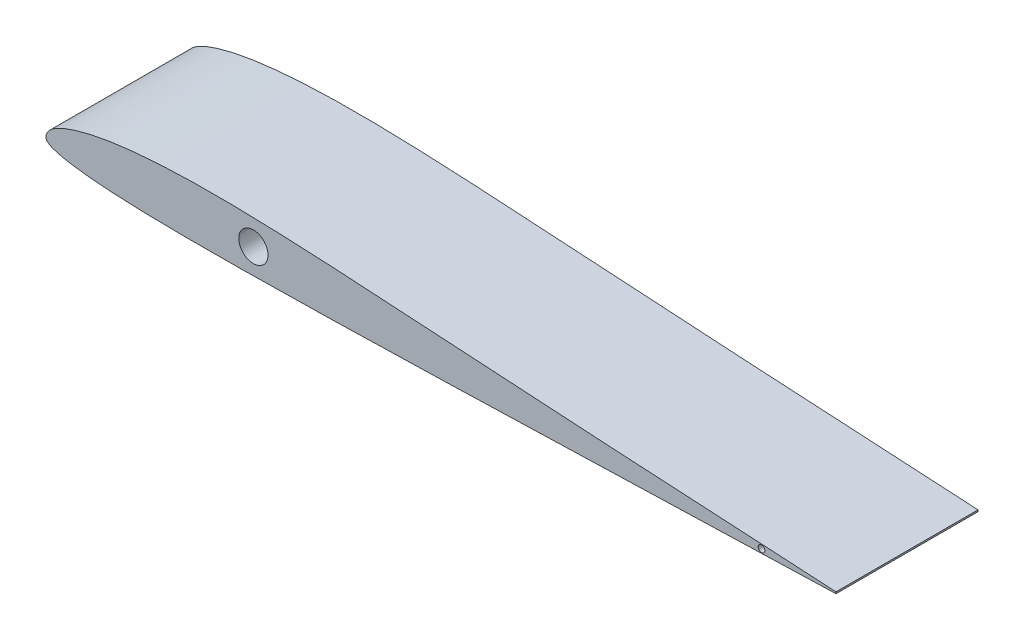
SolidWorks part; units mm, degrees
material "Polyurethane Foam Flexible"
ref_plane "Front Plane" through (0, 0, 0) normal (0, 0, 1) x (1, 0, 0)
ref_plane "Top Plane" through (0, 0, 0) normal (0, 1, 0) x (1, 0, 0)
ref_plane "Right Plane" through (0, 0, 0) normal (1, 0, 0) x (0, 0, -1)
curve "ht32-8-imported"
  spline degree 3 poles (203.2026, 0.2115, 0) (202.75, 0.2358, 0) (201.4822, 0.3036, 0) (199.2299, 0.4276, 0) (196.3046, 0.5865, 0) (192.9787, 0.7694, 0) (189.375, 0.9706, 0) (185.6129, 1.1785, 0) (181.7737, 1.3957, 0) (177.8996, 1.6147, 0) (174.01, 1.8354, 0) (170.1132, 2.0552, 0) (166.2133, 2.2775, 0) (162.3117, 2.4986, 0) (158.4107, 2.722, 0) (154.5106, 2.9441, 0) (150.6142, 3.1678, 0) (146.7204, 3.3936, 0) (142.8309, 3.617, 0) (138.944, 3.8454, 0) (135.0595, 4.0721, 0) (131.1775, 4.3012, 0) (127.2967, 4.5315, 0) (123.4189, 4.7649, 0) (119.5421, 5.0008, 0) (115.6675, 5.2398, 0) (111.7949, 5.4816, 0) (107.9236, 5.7247, 0) (104.0572, 5.9681, 0) (100.1894, 6.212, 0) (96.3188, 6.4543, 0) (92.4477, 6.6946, 0) (88.584, 6.9322, 0) (84.7415, 7.1637, 0) (80.9229, 7.3889, 0) (77.3978, 7.5906, 0) (74.5229, 7.7493, 0) (71.9946, 7.8843, 0) (69.1241, 8.0324, 0) (65.5083, 8.2076, 0) (61.4852, 8.3831, 0) (57.5218, 8.5328, 0) (53.6734, 8.652, 0) (49.9058, 8.739, 0) (46.181, 8.7912, 0) (42.491, 8.8047, 0) (38.8468, 8.7742, 0) (35.2596, 8.6962, 0) (31.7561, 8.5671, 0) (28.3661, 8.3856, 0) (25.1292, 8.152, 0) (22.0798, 7.8688, 0) (19.2587, 7.5428, 0) (16.7019, 7.1837, 0) (14.4336, 6.8058, 0) (12.4541, 6.4216, 0) (10.7471, 6.0418, 0) (9.283, 5.6741, 0) (8.0264, 5.3216, 0) (6.9394, 4.9844, 0) (5.9876, 4.6599, 0) (5.1429, 4.3427, 0) (4.3754, 4.0301, 0) (3.6577, 3.7081, 0) (2.9646, 3.3607, 0) (2.2868, 2.9708, 0) (1.6384, 2.5305, 0) (1.05, 2.0355, 0) (0.5511, 1.4823, 0) (0.1821, 0.8795, 0) (0.0202, 0.3651, 0) (-0.0065, -0.0193, 0) (0.0194, -0.3136, 0) (0.1268, -0.6144, 0) (0.297, -0.8546, 0) (0.4742, -1.036, 0) (0.6922, -1.2054, 0) (0.9846, -1.3848, 0) (1.3525, -1.5668, 0) (1.7794, -1.7448, 0) (2.2605, -1.9172, 0) (2.8067, -2.0876, 0) (3.4413, -2.2602, 0) (4.1881, -2.438, 0) (5.0669, -2.6215, 0) (6.0922, -2.8069, 0) (7.2766, -2.9931, 0) (8.6343, -3.178, 0) (10.1869, -3.3594, 0) (11.9608, -3.5369, 0) (13.9882, -3.7077, 0) (16.2949, -3.8689, 0) (18.8937, -4.0155, 0) (21.7662, -4.1437, 0) (24.8729, -4.2492, 0) (28.1584, -4.3297, 0) (31.5775, -4.3867, 0) (35.0914, -4.4207, 0) (38.6791, -4.4351, 0) (42.3216, -4.4311, 0) (46.0126, -4.4125, 0) (49.7579, -4.3795, 0) (53.5805, -4.3372, 0) (57.5149, -4.2842, 0) (61.5959, -4.2202, 0) (65.8841, -4.1445, 0) (69.584, -4.0721, 0) (72.8088, -4.005, 0) (75.5799, -3.9448, 0) (78.7708, -3.8727, 0) (82.2137, -3.7909, 0) (85.8123, -3.7021, 0) (89.4548, -3.6091, 0) (93.1502, -3.5116, 0) (96.8889, -3.4111, 0) (100.657, -3.3069, 0) (104.4397, -3.2018, 0) (108.2248, -3.0945, 0) (112.0082, -2.9863, 0) (115.791, -2.8766, 0) (119.5782, -2.7658, 0) (123.3765, -2.6523, 0) (127.1945, -2.5376, 0) (131.0416, -2.42, 0) (134.9198, -2.302, 0) (138.8194, -2.1823, 0) (142.7263, -2.0602, 0) (146.6334, -1.9373, 0) (150.5405, -1.8169, 0) (154.4476, -1.6935, 0) (158.3547, -1.5735, 0) (162.2615, -1.4515, 0) (166.1675, -1.3317, 0) (170.0718, -1.2089, 0) (173.9729, -1.0897, 0) (177.8669, -0.9678, 0) (181.7453, -0.8488, 0) (185.5889, -0.7312, 0) (189.3549, -0.6169, 0) (192.9626, -0.5096, 0) (196.292, -0.413, 0) (199.2203, -0.3248, 0) (201.4752, -0.2617, 0) (202.7443, -0.2247, 0) (203.1974, -0.2115, 0) knots 0 0 0 0 0.003316 0.009286 0.0165 0.024744 0.033651 0.0429 0.052304 0.061778 0.071282 0.080801 0.090326 0.099855 0.109385 0.118907 0.128429 0.137932 0.147436 0.156926 0.166412 0.175898 0.185369 0.194848 0.204314 0.213779 0.223243 0.232695 0.242152 0.25158 0.261042 0.270519 0.279949 0.289356 0.298677 0.307928 0.315183 0.319737 0.326448 0.336207 0.346216 0.355902 0.365219 0.374379 0.383467 0.392467 0.401369 0.410123 0.41871 0.427012 0.434953 0.442447 0.449411 0.455723 0.46133 0.466229 0.470471 0.47412 0.47727 0.480016 0.482444 0.484624 0.486615 0.488504 0.490376 0.492284 0.49422 0.496102 0.497896 0.499646 0.501237 0.501776 0.502457 0.503386 0.504071 0.504595 0.505236 0.506086 0.5071 0.508235 0.509467 0.510837 0.512419 0.514277 0.516452 0.518985 0.521897 0.525221 0.529007 0.53333 0.538261 0.543889 0.550243 0.557299 0.56492 0.57298 0.581338 0.589931 0.598683 0.607581 0.616575 0.625681 0.634977 0.644537 0.654462 0.664831 0.675908 0.681531 0.688425 0.696181 0.704877 0.713615 0.722511 0.731528 0.740655 0.749867 0.759101 0.768335 0.777565 0.786786 0.796016 0.805278 0.814581 0.823955 0.833431 0.842961 0.852492 0.862023 0.871554 0.881085 0.890615 0.900146 0.909675 0.9192 0.928718 0.938223 0.947696 0.9571 0.96635 0.975256 0.9835 0.990713 0.996685 1 1 1 1
sketch "Sketch3" plane through (0, 0, 0) normal (0, 0, 1) x (1, 0, 0)
  line L3 (203.2026, 0.2115) -> (203.1974, -0.2115)
  spline S0 degree 3 poles (334.6154, -3985.5649) (434.4726, 3.4305) (316.9129, -6.0481) (199.2299, 0.4276) (196.3046, 0.5865) (192.9787, 0.7694) (189.375, 0.9706) (185.6129, 1.1785) (181.7737, 1.3957) (177.8996, 1.6147) (174.01, 1.8354) (170.1132, 2.0552) (166.2133, 2.2775) (162.3117, 2.4986) (158.4107, 2.722) (154.5106, 2.9441) (150.6142, 3.1678) (146.7204, 3.3936) (142.8309, 3.617) (138.944, 3.8454) (135.0595, 4.0721) (131.1775, 4.3012) (127.2967, 4.5315) (123.4189, 4.7649) (119.5421, 5.0008) (115.6675, 5.2398) (111.7949, 5.4816) (107.9236, 5.7247) (104.0572, 5.9681) (100.1894, 6.212) (96.3188, 6.4543) (92.4477, 6.6946) (88.584, 6.9322) (84.7415, 7.1637) (80.9229, 7.3889) (77.3978, 7.5906) (74.5229, 7.7493) (71.9946, 7.8843) (69.1241, 8.0324) (65.5083, 8.2076) (61.4852, 8.3831) (57.5218, 8.5328) (53.6734, 8.652) (49.9058, 8.739) (46.181, 8.7912) (42.491, 8.8047) (38.8468, 8.7742) (35.2596, 8.6962) (31.7561, 8.5671) (28.3661, 8.3856) (25.1292, 8.152) (22.0798, 7.8688) (19.2587, 7.5428) (16.7019, 7.1837) (14.4336, 6.8058) (12.4541, 6.4216) (10.7471, 6.0418) (9.283, 5.6741) (8.0264, 5.3216) (6.9394, 4.9844) (5.9876, 4.6599) (5.1429, 4.3427) (4.3754, 4.0301) (3.6577, 3.7081) (2.9646, 3.3607) (2.2868, 2.9708) (1.6384, 2.5305) (1.05, 2.0355) (0.5511, 1.4823) (0.1821, 0.8795) (0.0202, 0.3651) (-0.0065, -0.0193) (0.0194, -0.3136) (0.1268, -0.6144) (0.297, -0.8546) (0.4742, -1.036) (0.6922, -1.2054) (0.9846, -1.3848) (1.3525, -1.5668) (1.7794, -1.7448) (2.2605, -1.9172) (2.8067, -2.0876) (3.4413, -2.2602) (4.1881, -2.438) (5.0669, -2.6215) (6.0922, -2.8069) (7.2766, -2.9931) (8.6343, -3.178) (10.1869, -3.3594) (11.9608, -3.5369) (13.9882, -3.7077) (16.2949, -3.8689) (18.8937, -4.0155) (21.7662, -4.1437) (24.8729, -4.2492) (28.1584, -4.3297) (31.5775, -4.3867) (35.0914, -4.4207) (38.6791, -4.4351) (42.3216, -4.4311) (46.0126, -4.4125) (49.7579, -4.3795) (53.5805, -4.3372) (57.5149, -4.2842) (61.5959, -4.2202) (65.8841, -4.1445) (69.584, -4.0721) (72.8088, -4.005) (75.5799, -3.9448) (78.7708, -3.8727) (82.2137, -3.7909) (85.8123, -3.7021) (89.4548, -3.6091) (93.1502, -3.5116) (96.8889, -3.4111) (100.657, -3.3069) (104.4397, -3.2018) (108.2248, -3.0945) (112.0082, -2.9863) (115.791, -2.8766) (119.5782, -2.7658) (123.3765, -2.6523) (127.1945, -2.5376) (131.0416, -2.42) (134.9198, -2.302) (138.8194, -2.1823) (142.7263, -2.0602) (146.6334, -1.9373) (150.5405, -1.8169) (154.4476, -1.6935) (158.3547, -1.5735) (162.2615, -1.4515) (166.1675, -1.3317) (170.0718, -1.2089) (173.9729, -1.0897) (177.8669, -0.9678) (181.7453, -0.8488) (185.5889, -0.7312) (189.3549, -0.6169) (192.9626, -0.5096) (196.292, -0.413) (199.2203, -0.3248) (326.9818, 3.2507) (453.3355, 21.4084) (694.2785, -3955.64) knots -0.845599 -0.845599 -0.845599 -0.845599 0.003316 0.009286 0.0165 0.024744 0.033651 0.0429 0.052304 0.061778 0.071282 0.080801 0.090326 0.099855 0.109385 0.118907 0.128429 0.137932 0.147436 0.156926 0.166412 0.175898 0.185369 0.194848 0.204314 0.213779 0.223243 0.232695 0.242152 0.25158 0.261042 0.270519 0.279949 0.289356 0.298677 0.307928 0.315183 0.319737 0.326448 0.336207 0.346216 0.355902 0.365219 0.374379 0.383467 0.392467 0.401369 0.410123 0.41871 0.427012 0.434953 0.442447 0.449411 0.455723 0.46133 0.466229 0.470471 0.47412 0.47727 0.480016 0.482444 0.484624 0.486615 0.488504 0.490376 0.492284 0.49422 0.496102 0.497896 0.499646 0.501237 0.501776 0.502457 0.503386 0.504071 0.504595 0.505236 0.506086 0.5071 0.508235 0.509467 0.510837 0.512419 0.514277 0.516452 0.518985 0.521897 0.525221 0.529007 0.53333 0.538261 0.543889 0.550243 0.557299 0.56492 0.57298 0.581338 0.589931 0.598683 0.607581 0.616575 0.625681 0.634977 0.644537 0.654462 0.664831 0.675908 0.681531 0.688425 0.696181 0.704877 0.713615 0.722511 0.731528 0.740655 0.749867 0.759101 0.768335 0.777565 0.786786 0.796016 0.805278 0.814581 0.823955 0.833431 0.842961 0.852492 0.862023 0.871554 0.881085 0.890615 0.900146 0.909675 0.9192 0.928718 0.938223 0.947696 0.9571 0.96635 0.975256 0.9835 0.990713 0.996685 1.918381 1.918381 1.918381 1.918381 only from (203.2026, 0.2115) to (203.1974, -0.2115) construction
  spline S1 degree 3 poles (203.2026, 0.2115) (202.75, 0.2358) (201.4822, 0.3036) (199.2299, 0.4276) (196.3046, 0.5865) (192.9787, 0.7694) (189.375, 0.9706) (185.6129, 1.1785) (181.7737, 1.3957) (177.8996, 1.6147) (174.01, 1.8354) (170.1132, 2.0552) (166.2133, 2.2775) (162.3117, 2.4986) (158.4107, 2.722) (154.5106, 2.9441) (150.6142, 3.1678) (146.7204, 3.3936) (142.8309, 3.617) (138.944, 3.8454) (135.0595, 4.0721) (131.1775, 4.3012) (127.2967, 4.5315) (123.4189, 4.7649) (119.5421, 5.0008) (115.6675, 5.2398) (111.7949, 5.4816) (107.9236, 5.7247) (104.0572, 5.9681) (100.1894, 6.212) (96.3188, 6.4543) (92.4477, 6.6946) (88.584, 6.9322) (84.7415, 7.1637) (80.9229, 7.3889) (77.3978, 7.5906) (74.5229, 7.7493) (71.9946, 7.8843) (69.1241, 8.0324) (65.5083, 8.2076) (61.4852, 8.3831) (57.5218, 8.5328) (53.6734, 8.652) (49.9058, 8.739) (46.181, 8.7912) (42.491, 8.8047) (38.8468, 8.7742) (35.2596, 8.6962) (31.7561, 8.5671) (28.3661, 8.3856) (25.1292, 8.152) (22.0798, 7.8688) (19.2587, 7.5428) (16.7019, 7.1837) (14.4336, 6.8058) (12.4541, 6.4216) (10.7471, 6.0418) (9.283, 5.6741) (8.0264, 5.3216) (6.9394, 4.9844) (5.9876, 4.6599) (5.1429, 4.3427) (4.3754, 4.0301) (3.6577, 3.7081) (2.9646, 3.3607) (2.2868, 2.9708) (1.6384, 2.5305) (1.05, 2.0355) (0.5511, 1.4823) (0.1821, 0.8795) (0.0202, 0.3651) (-0.0065, -0.0193) (0.0194, -0.3136) (0.1268, -0.6144) (0.297, -0.8546) (0.4742, -1.036) (0.6922, -1.2054) (0.9846, -1.3848) (1.3525, -1.5668) (1.7794, -1.7448) (2.2605, -1.9172) (2.8067, -2.0876) (3.4413, -2.2602) (4.1881, -2.438) (5.0669, -2.6215) (6.0922, -2.8069) (7.2766, -2.9931) (8.6343, -3.178) (10.1869, -3.3594) (11.9608, -3.5369) (13.9882, -3.7077) (16.2949, -3.8689) (18.8937, -4.0155) (21.7662, -4.1437) (24.8729, -4.2492) (28.1584, -4.3297) (31.5775, -4.3867) (35.0914, -4.4207) (38.6791, -4.4351) (42.3216, -4.4311) (46.0126, -4.4125) (49.7579, -4.3795) (53.5805, -4.3372) (57.5149, -4.2842) (61.5959, -4.2202) (65.8841, -4.1445) (69.584, -4.0721) (72.8088, -4.005) (75.5799, -3.9448) (78.7708, -3.8727) (82.2137, -3.7909) (85.8123, -3.7021) (89.4548, -3.6091) (93.1502, -3.5116) (96.8889, -3.4111) (100.657, -3.3069) (104.4397, -3.2018) (108.2248, -3.0945) (112.0082, -2.9863) (115.791, -2.8766) (119.5782, -2.7658) (123.3765, -2.6523) (127.1945, -2.5376) (131.0416, -2.42) (134.9198, -2.302) (138.8194, -2.1823) (142.7263, -2.0602) (146.6334, -1.9373) (150.5405, -1.8169) (154.4476, -1.6935) (158.3547, -1.5735) (162.2615, -1.4515) (166.1675, -1.3317) (170.0718, -1.2089) (173.9729, -1.0897) (177.8669, -0.9678) (181.7453, -0.8488) (185.5889, -0.7312) (189.3549, -0.6169) (192.9626, -0.5096) (196.292, -0.413) (199.2203, -0.3248) (201.4752, -0.2617) (202.7443, -0.2247) (203.1974, -0.2115) knots 0 0 0 0 0.003316 0.009286 0.0165 0.024744 0.033651 0.0429 0.052304 0.061778 0.071282 0.080801 0.090326 0.099855 0.109385 0.118907 0.128429 0.137932 0.147436 0.156926 0.166412 0.175898 0.185369 0.194848 0.204314 0.213779 0.223243 0.232695 0.242152 0.25158 0.261042 0.270519 0.279949 0.289356 0.298677 0.307928 0.315183 0.319737 0.326448 0.336207 0.346216 0.355902 0.365219 0.374379 0.383467 0.392467 0.401369 0.410123 0.41871 0.427012 0.434953 0.442447 0.449411 0.455723 0.46133 0.466229 0.470471 0.47412 0.47727 0.480016 0.482444 0.484624 0.486615 0.488504 0.490376 0.492284 0.49422 0.496102 0.497896 0.499646 0.501237 0.501776 0.502457 0.503386 0.504071 0.504595 0.505236 0.506086 0.5071 0.508235 0.509467 0.510837 0.512419 0.514277 0.516452 0.518985 0.521897 0.525221 0.529007 0.53333 0.538261 0.543889 0.550243 0.557299 0.56492 0.57298 0.581338 0.589931 0.598683 0.607581 0.616575 0.625681 0.634977 0.644537 0.654462 0.664831 0.675908 0.681531 0.688425 0.696181 0.704877 0.713615 0.722511 0.731528 0.740655 0.749867 0.759101 0.768335 0.777565 0.786786 0.796016 0.805278 0.814581 0.823955 0.833431 0.842961 0.852492 0.862023 0.871554 0.881085 0.890615 0.900146 0.909675 0.9192 0.928718 0.938223 0.947696 0.9571 0.96635 0.975256 0.9835 0.990713 0.996685 1 1 1 1
extrude "Airfoil" add sketch "Sketch3" along normal blind 36.5252
sketch "Sketch8" plane through (0, 0, 0) normal (0, 0, -1) x (-1, 0, 0)
  line L0 (0, 16.6795) -> (0, -1.637) construction
  line L2 (-53.34, 2.1587) -> (-53.34, 8.6559) construction
  line L3 (-53.34, 2.1587) -> (-53.34, -4.3386) construction
  circle A0 centre (-53.34, 2.1587) radius 3.7592
  spline S2 degree 3 poles (-203.2026, 0.2115) (-202.75, 0.2358) (-201.4822, 0.3036) (-199.2299, 0.4276) (-196.3046, 0.5865) (-192.9787, 0.7694) (-189.375, 0.9706) (-185.6129, 1.1785) (-181.7737, 1.3957) (-177.8996, 1.6147) (-174.01, 1.8354) (-170.1132, 2.0552) (-166.2133, 2.2775) (-162.3117, 2.4986) (-158.4107, 2.722) (-154.5106, 2.9441) (-150.6142, 3.1678) (-146.7204, 3.3936) (-142.8309, 3.617) (-138.944, 3.8454) (-135.0595, 4.0721) (-131.1775, 4.3012) (-127.2967, 4.5315) (-123.4189, 4.7649) (-119.5421, 5.0008) (-115.6675, 5.2398) (-111.7949, 5.4816) (-107.9236, 5.7247) (-104.0572, 5.9681) (-100.1894, 6.212) (-96.3188, 6.4543) (-92.4477, 6.6946) (-88.584, 6.9322) (-84.7415, 7.1637) (-80.9229, 7.3889) (-77.3978, 7.5906) (-74.5229, 7.7493) (-71.9946, 7.8843) (-69.1241, 8.0324) (-65.5083, 8.2076) (-61.4852, 8.3831) (-57.5218, 8.5328) (-53.6734, 8.652) (-49.9058, 8.739) (-46.181, 8.7912) (-42.491, 8.8047) (-38.8468, 8.7742) (-35.2596, 8.6962) (-31.7561, 8.5671) (-28.3661, 8.3856) (-25.1292, 8.152) (-22.0798, 7.8688) (-19.2587, 7.5428) (-16.7019, 7.1837) (-14.4336, 6.8058) (-12.4541, 6.4216) (-10.7471, 6.0418) (-9.283, 5.6741) (-8.0264, 5.3216) (-6.9394, 4.9844) (-5.9876, 4.6599) (-5.1429, 4.3427) (-4.3754, 4.0301) (-3.6577, 3.7081) (-2.9646, 3.3607) (-2.2868, 2.9708) (-1.6384, 2.5305) (-1.05, 2.0355) (-0.5511, 1.4823) (-0.1821, 0.8795) (-0.0202, 0.3651) (0.0065, -0.0193) (-0.0194, -0.3136) (-0.1268, -0.6144) (-0.297, -0.8546) (-0.4742, -1.036) (-0.6922, -1.2054) (-0.9846, -1.3848) (-1.3525, -1.5668) (-1.7794, -1.7448) (-2.2605, -1.9172) (-2.8067, -2.0876) (-3.4413, -2.2602) (-4.1881, -2.438) (-5.0669, -2.6215) (-6.0922, -2.8069) (-7.2766, -2.9931) (-8.6343, -3.178) (-10.1869, -3.3594) (-11.9608, -3.5369) (-13.9882, -3.7077) (-16.2949, -3.8689) (-18.8937, -4.0155) (-21.7662, -4.1437) (-24.8729, -4.2492) (-28.1584, -4.3297) (-31.5775, -4.3867) (-35.0914, -4.4207) (-38.6791, -4.4351) (-42.3216, -4.4311) (-46.0126, -4.4125) (-49.7579, -4.3795) (-53.5805, -4.3372) (-57.5149, -4.2842) (-61.5959, -4.2202) (-65.8841, -4.1445) (-69.584, -4.0721) (-72.8088, -4.005) (-75.5799, -3.9448) (-78.7708, -3.8727) (-82.2137, -3.7909) (-85.8123, -3.7021) (-89.4548, -3.6091) (-93.1502, -3.5116) (-96.8889, -3.4111) (-100.657, -3.3069) (-104.4397, -3.2018) (-108.2248, -3.0945) (-112.0082, -2.9863) (-115.791, -2.8766) (-119.5782, -2.7658) (-123.3765, -2.6523) (-127.1945, -2.5376) (-131.0416, -2.42) (-134.9198, -2.302) (-138.8194, -2.1823) (-142.7263, -2.0602) (-146.6334, -1.9373) (-150.5405, -1.8169) (-154.4476, -1.6935) (-158.3547, -1.5735) (-162.2615, -1.4515) (-166.1675, -1.3317) (-170.0718, -1.2089) (-173.9729, -1.0897) (-177.8669, -0.9678) (-181.7453, -0.8488) (-185.5889, -0.7312) (-189.3549, -0.6169) (-192.9626, -0.5096) (-196.292, -0.413) (-199.2203, -0.3248) (-201.4752, -0.2617) (-202.7443, -0.2247) (-203.1974, -0.2115) knots 0 0 0 0 0.003316 0.009286 0.0165 0.024744 0.033651 0.0429 0.052304 0.061778 0.071282 0.080801 0.090326 0.099855 0.109385 0.118907 0.128429 0.137932 0.147436 0.156926 0.166412 0.175898 0.185369 0.194848 0.204314 0.213779 0.223243 0.232695 0.242152 0.25158 0.261042 0.270519 0.279949 0.289356 0.298677 0.307928 0.315183 0.319737 0.326448 0.336207 0.346216 0.355902 0.365219 0.374379 0.383467 0.392467 0.401369 0.410123 0.41871 0.427012 0.434953 0.442447 0.449411 0.455723 0.46133 0.466229 0.470471 0.47412 0.47727 0.480016 0.482444 0.484624 0.486615 0.488504 0.490376 0.492284 0.49422 0.496102 0.497896 0.499646 0.501237 0.501776 0.502457 0.503386 0.504071 0.504595 0.505236 0.506086 0.5071 0.508235 0.509467 0.510837 0.512419 0.514277 0.516452 0.518985 0.521897 0.525221 0.529007 0.53333 0.538261 0.543889 0.550243 0.557299 0.56492 0.57298 0.581338 0.589931 0.598683 0.607581 0.616575 0.625681 0.634977 0.644537 0.654462 0.664831 0.675908 0.681531 0.688425 0.696181 0.704877 0.713615 0.722511 0.731528 0.740655 0.749867 0.759101 0.768335 0.777565 0.786786 0.796016 0.805278 0.814581 0.823955 0.833431 0.842961 0.852492 0.862023 0.871554 0.881085 0.890615 0.900146 0.909675 0.9192 0.928718 0.938223 0.947696 0.9571 0.96635 0.975256 0.9835 0.990713 0.996685 1 1 1 1 construction
  dimension "D1" = 7.5184
  dimension "D2" = 53.34
extrude "Camera Channel" cut sketch "Sketch8" against normal up to next
sketch "Sketch9" plane through (0, 0, 0) normal (0, 0, -1) x (-1, 0, 0)
  line L0 (-184.051, 1.108) -> (-184.051, 1.2671) construction
  line L1 (-184.051, -0.6192) -> (-184.051, -0.7783) construction
  circle A0 centre (-184.051, 0.2444) radius 0.8636
  spline S0 degree 3 poles (-370.7177, -1986.1352) (-386.1593, 0.2045) (-292.9152, -4.7275) (-199.2299, 0.4276) (-196.3046, 0.5865) (-192.9787, 0.7694) (-189.375, 0.9706) (-185.6129, 1.1785) (-181.7737, 1.3957) (-177.8996, 1.6147) (-174.01, 1.8354) (-170.1132, 2.0552) (-166.2133, 2.2775) (-162.3117, 2.4986) (-158.4107, 2.722) (-154.5106, 2.9441) (-150.6142, 3.1678) (-146.7204, 3.3936) (-142.8309, 3.617) (-138.944, 3.8454) (-135.0595, 4.0721) (-131.1775, 4.3012) (-127.2967, 4.5315) (-123.4189, 4.7649) (-119.5421, 5.0008) (-115.6675, 5.2398) (-111.7949, 5.4816) (-107.9236, 5.7247) (-104.0572, 5.9681) (-100.1894, 6.212) (-96.3188, 6.4543) (-92.4477, 6.6946) (-88.584, 6.9322) (-84.7415, 7.1637) (-80.9229, 7.3889) (-77.3978, 7.5906) (-74.5229, 7.7493) (-71.9946, 7.8843) (-69.1241, 8.0324) (-65.5083, 8.2076) (-61.4852, 8.3831) (-57.5218, 8.5328) (-53.6734, 8.652) (-49.9058, 8.739) (-46.181, 8.7912) (-42.491, 8.8047) (-38.8468, 8.7742) (-35.2596, 8.6962) (-31.7561, 8.5671) (-28.3661, 8.3856) (-25.1292, 8.152) (-22.0798, 7.8688) (-19.2587, 7.5428) (-16.7019, 7.1837) (-14.4336, 6.8058) (-12.4541, 6.4216) (-10.7471, 6.0418) (-9.283, 5.6741) (-8.0264, 5.3216) (-6.9394, 4.9844) (-5.9876, 4.6599) (-5.1429, 4.3427) (-4.3754, 4.0301) (-3.6577, 3.7081) (-2.9646, 3.3607) (-2.2868, 2.9708) (-1.6384, 2.5305) (-1.05, 2.0355) (-0.5511, 1.4823) (-0.1821, 0.8795) (-0.0202, 0.3651) (0.0065, -0.0193) (-0.0194, -0.3136) (-0.1268, -0.6144) (-0.297, -0.8546) (-0.4742, -1.036) (-0.6922, -1.2054) (-0.9846, -1.3848) (-1.3525, -1.5668) (-1.7794, -1.7448) (-2.2605, -1.9172) (-2.8067, -2.0876) (-3.4413, -2.2602) (-4.1881, -2.438) (-5.0669, -2.6215) (-6.0922, -2.8069) (-7.2766, -2.9931) (-8.6343, -3.178) (-10.1869, -3.3594) (-11.9608, -3.5369) (-13.9882, -3.7077) (-16.2949, -3.8689) (-18.8937, -4.0155) (-21.7662, -4.1437) (-24.8729, -4.2492) (-28.1584, -4.3297) (-31.5775, -4.3867) (-35.0914, -4.4207) (-38.6791, -4.4351) (-42.3216, -4.4311) (-46.0126, -4.4125) (-49.7579, -4.3795) (-53.5805, -4.3372) (-57.5149, -4.2842) (-61.5959, -4.2202) (-65.8841, -4.1445) (-69.584, -4.0721) (-72.8088, -4.005) (-75.5799, -3.9448) (-78.7708, -3.8727) (-82.2137, -3.7909) (-85.8123, -3.7021) (-89.4548, -3.6091) (-93.1502, -3.5116) (-96.8889, -3.4111) (-100.657, -3.3069) (-104.4397, -3.2018) (-108.2248, -3.0945) (-112.0082, -2.9863) (-115.791, -2.8766) (-119.5782, -2.7658) (-123.3765, -2.6523) (-127.1945, -2.5376) (-131.0416, -2.42) (-134.9198, -2.302) (-138.8194, -2.1823) (-142.7263, -2.0602) (-146.6334, -1.9373) (-150.5405, -1.8169) (-154.4476, -1.6935) (-158.3547, -1.5735) (-162.2615, -1.4515) (-166.1675, -1.3317) (-170.0718, -1.2089) (-173.9729, -1.0897) (-177.8669, -0.9678) (-181.7453, -0.8488) (-185.5889, -0.7312) (-189.3549, -0.6169) (-192.9626, -0.5096) (-196.292, -0.413) (-199.2203, -0.3248) (-300.851, 2.5194) (-401.2299, 14.5438) (-558.1905, -1960.49) knots -0.669801 -0.669801 -0.669801 -0.669801 0.003316 0.009286 0.0165 0.024744 0.033651 0.0429 0.052304 0.061778 0.071282 0.080801 0.090326 0.099855 0.109385 0.118907 0.128429 0.137932 0.147436 0.156926 0.166412 0.175898 0.185369 0.194848 0.204314 0.213779 0.223243 0.232695 0.242152 0.25158 0.261042 0.270519 0.279949 0.289356 0.298677 0.307928 0.315183 0.319737 0.326448 0.336207 0.346216 0.355902 0.365219 0.374379 0.383467 0.392467 0.401369 0.410123 0.41871 0.427012 0.434953 0.442447 0.449411 0.455723 0.46133 0.466229 0.470471 0.47412 0.47727 0.480016 0.482444 0.484624 0.486615 0.488504 0.490376 0.492284 0.49422 0.496102 0.497896 0.499646 0.501237 0.501776 0.502457 0.503386 0.504071 0.504595 0.505236 0.506086 0.5071 0.508235 0.509467 0.510837 0.512419 0.514277 0.516452 0.518985 0.521897 0.525221 0.529007 0.53333 0.538261 0.543889 0.550243 0.557299 0.56492 0.57298 0.581338 0.589931 0.598683 0.607581 0.616575 0.625681 0.634977 0.644537 0.654462 0.664831 0.675908 0.681531 0.688425 0.696181 0.704877 0.713615 0.722511 0.731528 0.740655 0.749867 0.759101 0.768335 0.777565 0.786786 0.796016 0.805278 0.814581 0.823955 0.833431 0.842961 0.852492 0.862023 0.871554 0.881085 0.890615 0.900146 0.909675 0.9192 0.928718 0.938223 0.947696 0.9571 0.96635 0.975256 0.9835 0.990713 0.996685 1.727171 1.727171 1.727171 1.727171 only from (-203.2026, 0.2115) to (-203.1974, -0.2115) construction
  spline S1 degree 3 poles (-203.2026, 0.2115) (-202.75, 0.2358) (-201.4822, 0.3036) (-199.2299, 0.4276) (-196.3046, 0.5865) (-192.9787, 0.7694) (-189.375, 0.9706) (-185.6129, 1.1785) (-181.7737, 1.3957) (-177.8996, 1.6147) (-174.01, 1.8354) (-170.1132, 2.0552) (-166.2133, 2.2775) (-162.3117, 2.4986) (-158.4107, 2.722) (-154.5106, 2.9441) (-150.6142, 3.1678) (-146.7204, 3.3936) (-142.8309, 3.617) (-138.944, 3.8454) (-135.0595, 4.0721) (-131.1775, 4.3012) (-127.2967, 4.5315) (-123.4189, 4.7649) (-119.5421, 5.0008) (-115.6675, 5.2398) (-111.7949, 5.4816) (-107.9236, 5.7247) (-104.0572, 5.9681) (-100.1894, 6.212) (-96.3188, 6.4543) (-92.4477, 6.6946) (-88.584, 6.9322) (-84.7415, 7.1637) (-80.9229, 7.3889) (-77.3978, 7.5906) (-74.5229, 7.7493) (-71.9946, 7.8843) (-69.1241, 8.0324) (-65.5083, 8.2076) (-61.4852, 8.3831) (-57.5218, 8.5328) (-53.6734, 8.652) (-49.9058, 8.739) (-46.181, 8.7912) (-42.491, 8.8047) (-38.8468, 8.7742) (-35.2596, 8.6962) (-31.7561, 8.5671) (-28.3661, 8.3856) (-25.1292, 8.152) (-22.0798, 7.8688) (-19.2587, 7.5428) (-16.7019, 7.1837) (-14.4336, 6.8058) (-12.4541, 6.4216) (-10.7471, 6.0418) (-9.283, 5.6741) (-8.0264, 5.3216) (-6.9394, 4.9844) (-5.9876, 4.6599) (-5.1429, 4.3427) (-4.3754, 4.0301) (-3.6577, 3.7081) (-2.9646, 3.3607) (-2.2868, 2.9708) (-1.6384, 2.5305) (-1.05, 2.0355) (-0.5511, 1.4823) (-0.1821, 0.8795) (-0.0202, 0.3651) (0.0065, -0.0193) (-0.0194, -0.3136) (-0.1268, -0.6144) (-0.297, -0.8546) (-0.4742, -1.036) (-0.6922, -1.2054) (-0.9846, -1.3848) (-1.3525, -1.5668) (-1.7794, -1.7448) (-2.2605, -1.9172) (-2.8067, -2.0876) (-3.4413, -2.2602) (-4.1881, -2.438) (-5.0669, -2.6215) (-6.0922, -2.8069) (-7.2766, -2.9931) (-8.6343, -3.178) (-10.1869, -3.3594) (-11.9608, -3.5369) (-13.9882, -3.7077) (-16.2949, -3.8689) (-18.8937, -4.0155) (-21.7662, -4.1437) (-24.8729, -4.2492) (-28.1584, -4.3297) (-31.5775, -4.3867) (-35.0914, -4.4207) (-38.6791, -4.4351) (-42.3216, -4.4311) (-46.0126, -4.4125) (-49.7579, -4.3795) (-53.5805, -4.3372) (-57.5149, -4.2842) (-61.5959, -4.2202) (-65.8841, -4.1445) (-69.584, -4.0721) (-72.8088, -4.005) (-75.5799, -3.9448) (-78.7708, -3.8727) (-82.2137, -3.7909) (-85.8123, -3.7021) (-89.4548, -3.6091) (-93.1502, -3.5116) (-96.8889, -3.4111) (-100.657, -3.3069) (-104.4397, -3.2018) (-108.2248, -3.0945) (-112.0082, -2.9863) (-115.791, -2.8766) (-119.5782, -2.7658) (-123.3765, -2.6523) (-127.1945, -2.5376) (-131.0416, -2.42) (-134.9198, -2.302) (-138.8194, -2.1823) (-142.7263, -2.0602) (-146.6334, -1.9373) (-150.5405, -1.8169) (-154.4476, -1.6935) (-158.3547, -1.5735) (-162.2615, -1.4515) (-166.1675, -1.3317) (-170.0718, -1.2089) (-173.9729, -1.0897) (-177.8669, -0.9678) (-181.7453, -0.8488) (-185.5889, -0.7312) (-189.3549, -0.6169) (-192.9626, -0.5096) (-196.292, -0.413) (-199.2203, -0.3248) (-201.4752, -0.2617) (-202.7443, -0.2247) (-203.1974, -0.2115) knots 0 0 0 0 0.003316 0.009286 0.0165 0.024744 0.033651 0.0429 0.052304 0.061778 0.071282 0.080801 0.090326 0.099855 0.109385 0.118907 0.128429 0.137932 0.147436 0.156926 0.166412 0.175898 0.185369 0.194848 0.204314 0.213779 0.223243 0.232695 0.242152 0.25158 0.261042 0.270519 0.279949 0.289356 0.298677 0.307928 0.315183 0.319737 0.326448 0.336207 0.346216 0.355902 0.365219 0.374379 0.383467 0.392467 0.401369 0.410123 0.41871 0.427012 0.434953 0.442447 0.449411 0.455723 0.46133 0.466229 0.470471 0.47412 0.47727 0.480016 0.482444 0.484624 0.486615 0.488504 0.490376 0.492284 0.49422 0.496102 0.497896 0.499646 0.501237 0.501776 0.502457 0.503386 0.504071 0.504595 0.505236 0.506086 0.5071 0.508235 0.509467 0.510837 0.512419 0.514277 0.516452 0.518985 0.521897 0.525221 0.529007 0.53333 0.538261 0.543889 0.550243 0.557299 0.56492 0.57298 0.581338 0.589931 0.598683 0.607581 0.616575 0.625681 0.634977 0.644537 0.654462 0.664831 0.675908 0.681531 0.688425 0.696181 0.704877 0.713615 0.722511 0.731528 0.740655 0.749867 0.759101 0.768335 0.777565 0.786786 0.796016 0.805278 0.814581 0.823955 0.833431 0.842961 0.852492 0.862023 0.871554 0.881085 0.890615 0.900146 0.909675 0.9192 0.928718 0.938223 0.947696 0.9571 0.96635 0.975256 0.9835 0.990713 0.996685 1 1 1 1 construction
  dimension "D2" = 1.7272
  dimension "D1" = 19.1516
extrude "Cut-Extrude1" cut sketch "Sketch9" against normal through all
